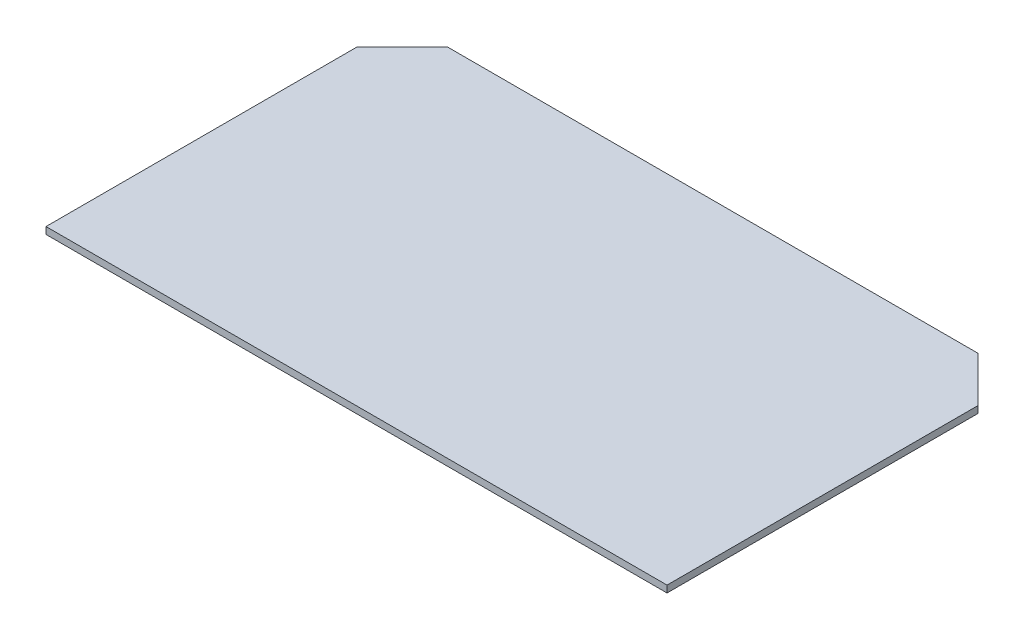
SolidWorks part; units mm, degrees
ref_plane "Front Plane" through (0, 0, 0) normal (0, 0, 1) x (1, 0, 0)
ref_plane "Top Plane" through (0, 0, 0) normal (0, 1, 0) x (1, 0, 0)
ref_plane "Right Plane" through (0, 0, 0) normal (1, 0, 0) x (0, 0, -1)
sketch "Sketch1" plane through (0, 0, 0) normal (0, 1, 0) x (1, 0, 0)
  line L0 (-46.2712, 22.8632) -> (-46.2712, -11.6808)
  line L1 (-46.2712, -11.6808) -> (22.7146, -11.6808)
  line L2 (22.7146, -11.6808) -> (22.7146, 22.8632)
  line L3 (22.7146, 22.8632) -> (17.6857, 27.8922)
  line L4 (17.6857, 27.8922) -> (-41.2423, 27.8922)
  line L5 (-41.2423, 27.8922) -> (-46.2712, 22.8632)
  dimension "D1" = 7.112
  dimension "D2" = 7.112
  dimension "D3" = 58.928
  dimension "D4" = 34.544
  dimension "D5" = 135
  dimension "D6" = 135
extrude "Boss-Extrude1" add sketch "Sketch1" along normal blind 0.762
